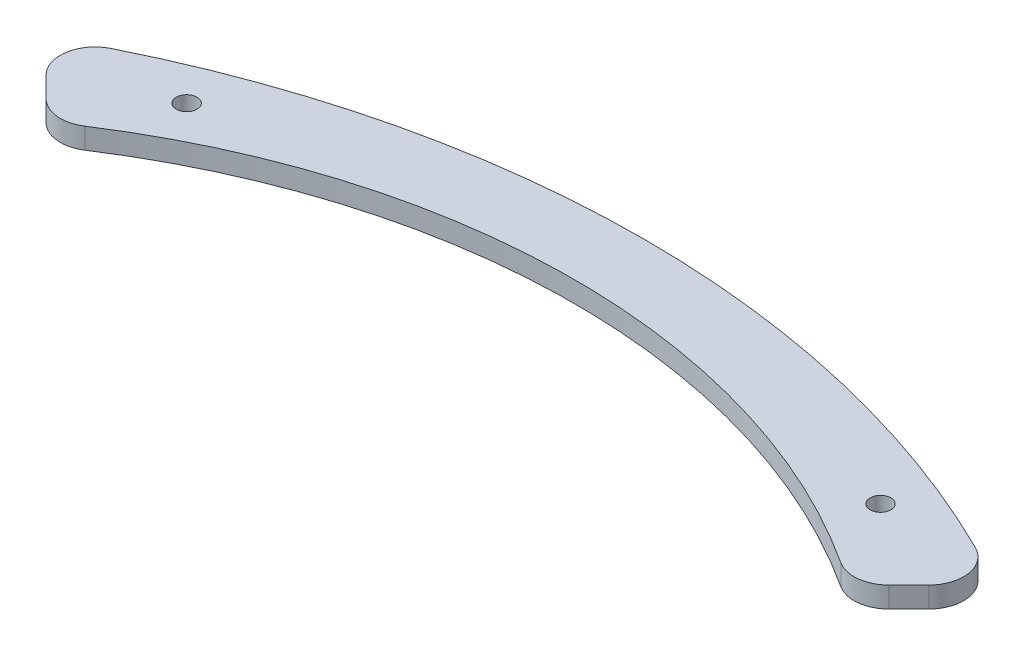
SolidWorks part; units mm, degrees
material "1060 Alloy"
ref_plane "Front Plane" through (0, 0, 0) normal (0, 0, 1) x (1, 0, 0)
ref_plane "Top Plane" through (0, 0, 0) normal (0, 1, 0) x (1, 0, 0)
ref_plane "Right Plane" through (0, 0, 0) normal (1, 0, 0) x (0, 0, -1)
sketch "Sketch1" plane through (0, 0, 0) normal (0, 1, 0) x (1, 0, 0)
  line L0 (-68.4085, 122.1486) -> (-57.8019, 111.542)
  line L1 (68.4085, 122.1486) -> (57.8019, 111.542)
  line L3 (0, 0) -> (-117.9329, 117.9329) construction
  line L4 (0, 0) -> (118.2874, 118.2874) construction
  line L5 (0, 0) -> (0, 174.1104) construction
  line L6 (-15, 129.1317) -> (15, 129.1317) construction
  line L7 (-15, 129.1317) -> (-15, 118.1317) construction
  line L8 (-15, 118.1317) -> (15, 118.1317) construction
  line L9 (15, 129.1317) -> (15, 118.1317) construction
  arc A0 (-68.4085, 122.1486) -> (68.4085, 122.1486) centre (0, 0) cw
  arc A1 (-57.8019, 111.542) -> (57.8019, 111.542) centre (0, 29.9396) cw
  circle A2 centre (0, 0) radius 130 construction
  dimension "D1" = 140
  dimension "D6" = 100
  dimension "D7" = 10
  dimension "D2" = 15
  dimension "D3" = 45
  dimension "D4" = 38
  dimension "D5" = 38
  dimension "D8" = 11
  dimension "D9" = 30
extrude "Boss-Extrude1" add sketch "Sketch1" along normal blind 3
fillet "Fillet1" radius 5 4 edges at (68.4085, 1.5, -122.1486) (57.8019, 1.5, -111.542) (-68.4085, 1.5, -122.1486) (-57.8019, 1.5, -111.542)
sketch "Sketch2" plane through (0, 3, 0) normal (0, 1, 0) x (1, 0, 0)
  circle A0 centre (-50, 124) radius 1.5
  circle A1 centre (50, 124) radius 1.5
  dimension "D1" = 3
  dimension "D2" = 124
  dimension "D3" = 50
  dimension "D4" = 50
extrude "Cut-Extrude1" cut sketch "Sketch2" against normal up to next
